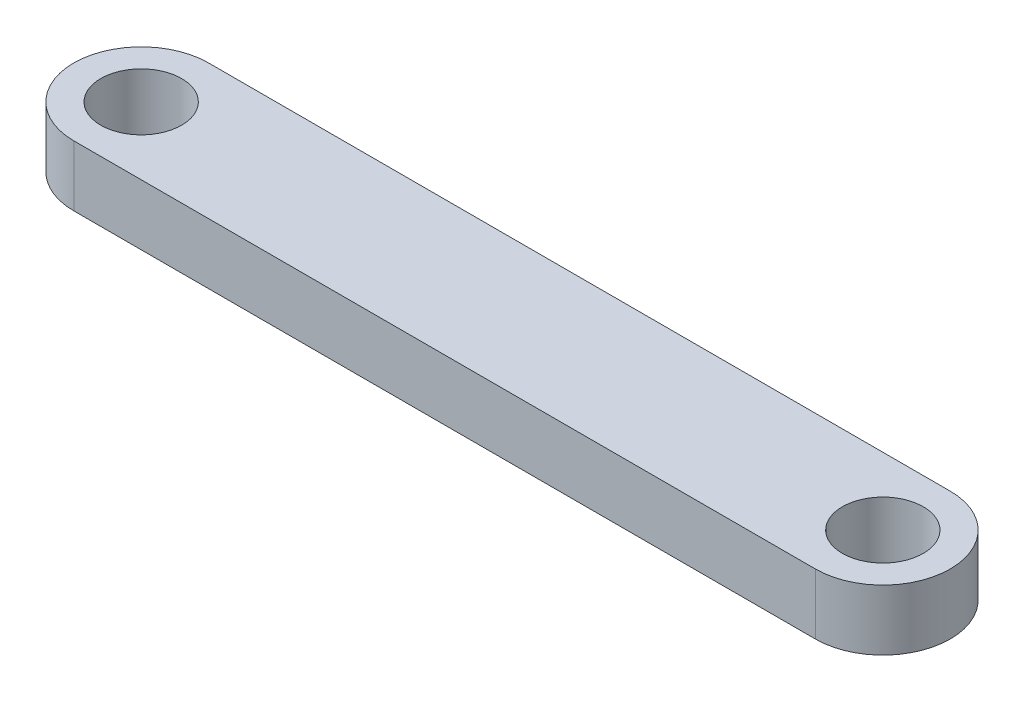
SolidWorks part; units mm, degrees
ref_plane "前视基准面" through (0, 0, 0) normal (0, 0, 1) x (1, 0, 0)
ref_plane "上视基准面" through (0, 0, 0) normal (0, 1, 0) x (1, 0, 0)
ref_plane "右视基准面" through (0, 0, 0) normal (1, 0, 0) x (0, 0, -1)
sketch "草图1" plane through (0, 0, 0) normal (0, 1, 0) x (1, 0, 0)
  line L1 (-30, 5) -> (25, 5)
  line L3 (-30, -5) -> (25, -5)
  line L6 (0, 0) -> (25, 5) construction
  arc A0 (-30, 5) -> (-30, -5) centre (-30, 0) ccw
  arc A1 (25, -5) -> (25, 5) centre (25, 0) ccw
  circle A2 centre (-30, 0) radius 3
  circle A3 centre (25, 0) radius 3
  point P0 (0, 0)
  dimension "D3" = 6
  dimension "D4" = 6
  dimension "D1" = 55
  dimension "D2" = 10
extrude "凸台-拉伸1" add sketch "草图1" along normal blind 4.5
